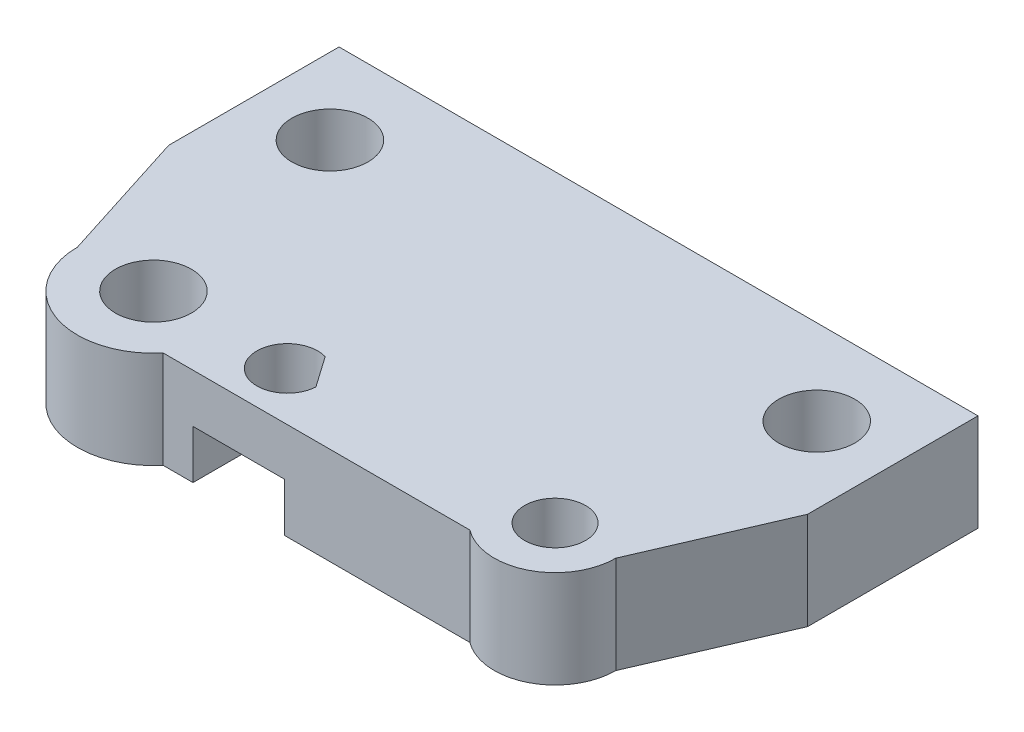
SolidWorks part; units mm, degrees
material "6061-T6 (SS)"
ref_plane "X-Y Datum" through (0, 0, 0) normal (0, 0, 1) x (1, 0, 0)
ref_plane "X-Z Datum" through (0, 0, 0) normal (0, 1, 0) x (1, 0, 0)
ref_plane "Y-Z Datum" through (0, 0, 0) normal (1, 0, 0) x (0, 0, -1)
sketch "Sketch1" plane through (0, 0, 0) normal (0, 1, 0) x (1, 0, 0)
  line L0 (38.1, -5.08) -> (6.099, -5.08)
  line L1 (54.2925, 13.97) -> (-12.3825, 13.97) construction
  line L4 (54.2925, 31.75) -> (-12.3825, 31.75)
  line L6 (46.355, 22.86) -> (-4.445, 22.86) construction
  line L7 (54.2925, 31.75) -> (54.2925, 13.97)
  line L8 (-12.3825, 31.75) -> (-12.3825, 13.97)
  line L19 (48.26, 0) -> (54.2925, 13.97)
  line L21 (-7.9375, 0) -> (-12.3825, 13.97)
  line L28 (17.1395, -0.1867) -> (14.8786, 3.0422)
  line L30 (16.5708, 1.8211) -> (13.97, 0) construction
  line L31 (16.009, 1.4277) -> (11.1341, 1.4277) construction
  circle A0 centre (0, 0) radius 3.9688
  circle A1 centre (41.91, 0) radius 3.175
  circle A2 centre (46.355, 22.86) radius 3.9688
  circle A3 centre (-4.445, 22.86) radius 3.9687
  arc A4 (48.26, 0) -> (38.1, -5.08) centre (41.91, 0) cw
  arc A5 (6.099, -5.08) -> (-7.9375, 0) centre (0, 0) cw
  arc A12 (17.1395, -0.1867) -> (14.8786, 3.0422) centre (13.97, 0) cw
  point P22 (16.009, 1.4277)
  dimension "D2" = 6.35
  dimension "D7" = 7.9375
  dimension "D8" = 6.35
  dimension "D12" = 0.6858
  dimension "D10" = 7.9375
  dimension "D17" = 35
  dimension "D19" = 7.9375
  dimension "D18" = 19.05
  dimension "D14" = 3.9418
  dimension "D20" = 7.9375
  dimension "D3" = 50.8
  dimension "D4" = 17.78
  dimension "D5" = 8.89
  dimension "D6" = 31.75
  dimension "D9" = 41.91
  dimension "D11" = 7.9375
  dimension "D13" = 3.175
  dimension "D15" = 13.97
  dimension "D16" = 5.08
  dimension "D21" = 4.445
  dimension "D22" = 66.644
  dimension "D23" = 72.35
extrude "Boss-Extrude1" add sketch "Sketch1" against normal blind 10.16
sketch "Sketch2" plane through (0, -10.16, 0) normal (0, -1, 0) x (1, 0, 0)
  line L0 (9.2075, 0) -> (9.2075, 5.08)
  line L1 (6.099, 5.08) -> (38.1, 5.08) construction
  line L2 (9.2075, 5.08) -> (18.7325, 5.08)
  line L3 (18.7325, 5.08) -> (18.7325, 0)
  arc A0 (9.2075, 0) -> (18.7325, 0) centre (13.97, 0) ccw
  dimension "D1" = 9.525
extrude "Cut-Extrude1" cut sketch "Sketch2" against normal blind 5.08
